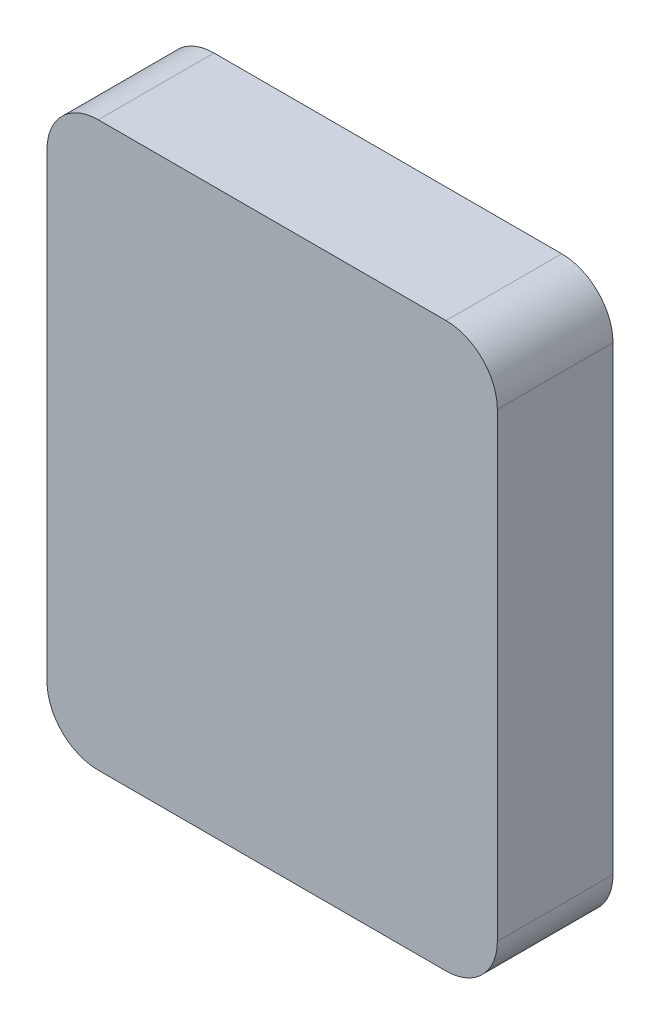
SolidWorks part; units mm, degrees
ref_plane "Front Plane" through (0, 0, 0) normal (0, 0, 1) x (1, 0, 0)
ref_plane "Top Plane" through (0, 0, 0) normal (0, 1, 0) x (1, 0, 0)
ref_plane "Right Plane" through (0, 0, 0) normal (1, 0, 0) x (0, 0, -1)
sketch "Sketch1" plane through (0, 0, 0) normal (0, 0, 1) x (1, 0, 0)
  line L0 (-24.4748, 46.647) -> (-24.4748, -16.233)
  line L1 (-17.4748, -23.233) -> (29.9852, -23.233)
  line L2 (36.9852, -16.233) -> (36.9852, 46.647)
  line L3 (29.9852, 53.647) -> (-17.4748, 53.647)
  arc A0 (-24.4748, 46.647) -> (-17.4748, 53.647) centre (-17.4748, 46.647) cw
  arc A1 (-24.4748, -16.233) -> (-17.4748, -23.233) centre (-17.4748, -16.233) ccw
  arc A2 (29.9852, -23.233) -> (36.9852, -16.233) centre (29.9852, -16.233) ccw
  arc A3 (36.9852, 46.647) -> (29.9852, 53.647) centre (29.9852, 46.647) ccw
  point P6 (-24.4748, 53.647)
  point P9 (-24.4748, -23.233)
  point P14 (36.9852, 53.647)
  dimension "D3" = 7
  dimension "D4" = 7
  dimension "D1" = 76.88
  dimension "D2" = 61.46
extrude "Boss-Extrude1" add sketch "Sketch1" along normal blind 15.7856
sketch "Sketch2" plane through (0, 0, 15.7856) normal (0, 0, 1) x (1, 0, 0)
  line L5 (54.318, 46.6716) -> (-3.142, 46.6716)
  line L6 (54.318, 46.6716) -> (54.318, -24.2084)
  line L7 (54.318, -24.2084) -> (-3.142, -24.2084)
  line L8 (-3.142, 46.6716) -> (-3.142, -24.2084)
  dimension "D1" = 70.88
  dimension "D2" = 57.46
